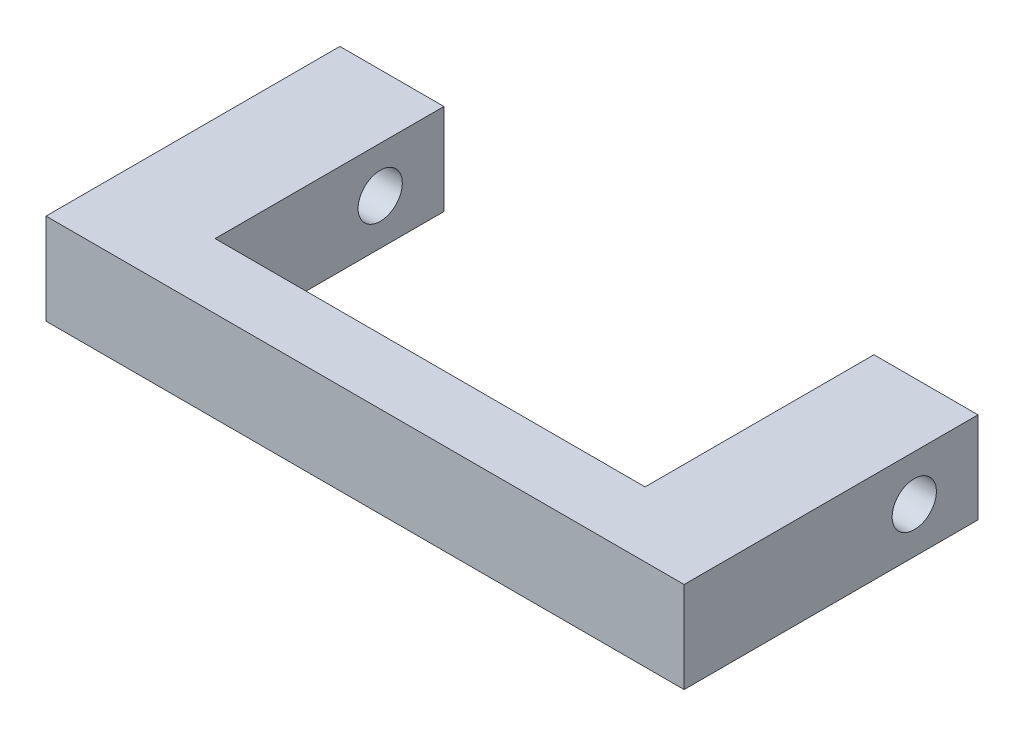
SolidWorks part; units mm, degrees
ref_plane "Front Plane" through (0, 0, 0) normal (0, 0, 1) x (1, 0, 0)
ref_plane "Top Plane" through (0, 0, 0) normal (0, 1, 0) x (1, 0, 0)
ref_plane "Right Plane" through (0, 0, 0) normal (1, 0, 0) x (0, 0, -1)
sketch "Sketch1" plane through (0, 0, 0) normal (0, 1, 0) x (1, 0, 0)
  line L0 (-87.25, -27.0052) -> (-87.25, -44.6052)
  line L1 (-87.25, -44.6052) -> (-54.181, -44.6052)
  line L2 (-54.181, -44.6052) -> (-54.181, -27.0052)
  line L3 (-54.181, -27.0052) -> (-46.181, -27.0052)
  line L4 (-46.181, -27.0052) -> (-46.181, -49.6052)
  line L5 (-46.181, -49.6052) -> (-64.006, -49.6052)
  line L6 (-87.25, -27.0052) -> (-95.25, -27.0052)
  line L7 (-95.25, -27.0052) -> (-95.25, -49.6052)
  line L8 (-95.25, -49.6052) -> (-77.425, -49.6052)
  line L39 (-77.425, -49.6052) -> (-64.006, -49.6052)
  dimension "D1" = 8
  dimension "D2" = 17.6
  dimension "D3" = 5
  dimension "D4" = 33.069
extrude "Boss-Extrude1" add sketch "Sketch1" along normal blind 7
sketch "Sketch3" plane through (-46.181, 0, 0) normal (1, 0, 0) x (0, 0, -1)
  line L0 (-27.0052, 7) -> (-27.0052, 0) construction
  line L1 (-49.6052, 7) -> (-27.0052, 7) construction
  line L2 (-49.6052, 0) -> (-27.0052, 0) construction
  circle A0 centre (-31.9052, 3.5) radius 1.7
  dimension "D1" = 3.4
  dimension "D3" = 3.5
  dimension "D4" = 3.5
  dimension "D2" = 4.9
extrude "Cut-Extrude2" cut sketch "Sketch3" against normal blind 60
